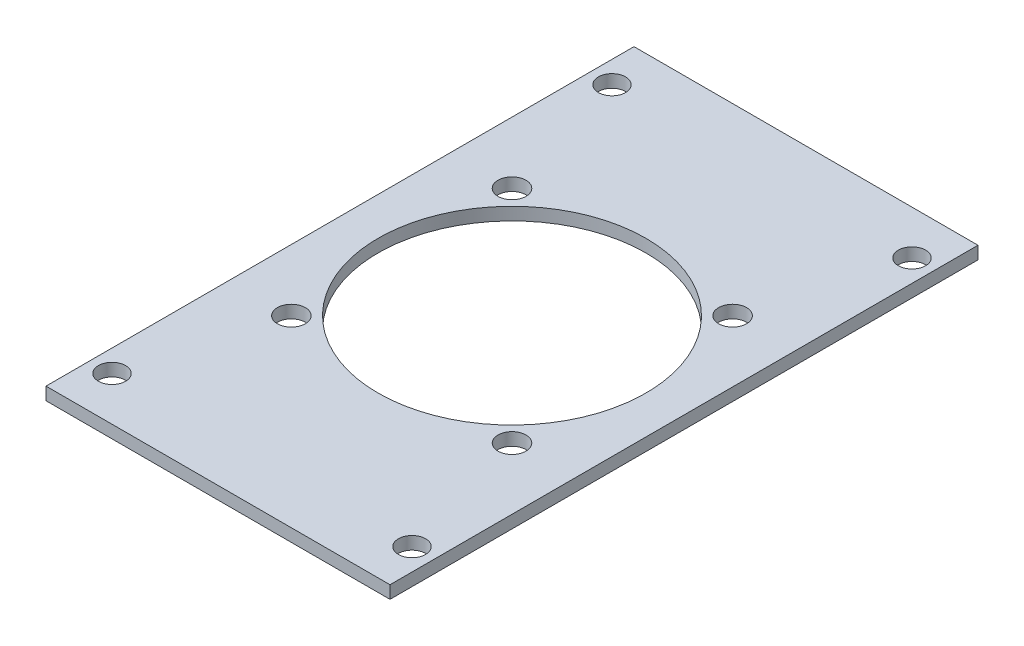
SolidWorks part; units mm, degrees
material "AISI 1045 Steel, cold drawn"
ref_plane "Frontal Plane" through (0, 0, 0) normal (0, 0, 1) x (1, 0, 0)
ref_plane "Horizontal Plane" through (0, 0, 0) normal (0, 1, 0) x (1, 0, 0)
ref_plane "Profile Plane" through (0, 0, 0) normal (1, 0, 0) x (0, 0, -1)
sketch "Sketch1" plane through (0, 0, 0) normal (0, 1, 0) x (1, 0, 0)
  line L1 (-43, -73.5) -> (43, -73.5)
  line L2 (-43, -73.5) -> (-43, 73.5)
  line L3 (-43, 73.5) -> (43, 73.5)
  line L4 (43, -73.5) -> (43, 73.5)
  line L5 (-43, -73.5) -> (43, 73.5) construction
  line L6 (-43, 73.5) -> (43, -73.5) construction
  circle A0 centre (0, 0) radius 33.5
  circle A1 centre (-37.5, -62.5) radius 3.4
  circle A2 centre (37.5, -62.5) radius 3.4
  circle A3 centre (-37.5, 62.5) radius 3.4
  circle A4 centre (37.5, 62.5) radius 3.4
  point P0 (0, 0)
  dimension "D1" = 67
  dimension "D5" = 6.8
  dimension "D2" = 86
  dimension "D3" = 147
  dimension "D4" = 75
  dimension "D6" = 125
  dimension "D7" = 62.5
  dimension "D8" = 37.5
extrude "Boss-Extrude1" add sketch "Sketch1" along normal blind 3.175
sketch "Sketch2" plane through (0, 3.175, 0) normal (0, 1, 0) x (1, 0, 0)
  line L0 (-27.5772, 27.5772) -> (0, 0) construction
  line L1 (0, 0) -> (0, 39) construction
  line L2 (0, 0) -> (-27.5772, 27.5772) construction
  circle A0 centre (0, 0) radius 39 construction
  circle A1 centre (-27.5772, 27.5772) radius 3.5
  circle A2 centre (27.5772, 27.5772) radius 3.5
  circle A3 centre (27.5772, -27.5772) radius 3.5
  circle A4 centre (-27.5772, -27.5772) radius 3.5
  dimension "D1" = 78
  dimension "D3" = 7
  dimension "D2" = 45
  dimension "D5" = 39
  dimension "D4" = 4
extrude "Cut-Extrude1" cut sketch "Sketch2" against normal blind 10
equation "\"WallThickness\"= 0.5cm"
equation "\"BottomPlateX\"= 3ft"
equation "\"BottomPlateZ\"= 2ft"
equation "\"BottomPlateHoleD\"=((\"ArmPlateX\")^2+(\"ArmPlateDepth\")^2)^.5+ 10mm"
equation "\"ActuatorPinD\"= 6.35mm"
equation "\"ActuatorPinL\"= 15cm"
equation "\"Box-X\"= 40cm"
equation "\"Box-Z\"= 20cm"
equation "\"Box-Y\"= 30cm"
equation "\"ArmPlateThickness\"= .125in"
equation "\"ArmPlateX\"= 18in"
equation "\"ArmPlateDepth\"= 7.1875in"
equation "\"DCMotor1D\"= 65mm"
equation "\"DCMotor1L\"= 215mm"
equation "\"DCMotor1ShaftL\"= 30mm"
equation "\"DCMotor2X\"= 68mm"
equation "\"DCMotor2D\"= 65mm"
equation "\"DCMotor2L\"= 208mm"
equation "\"DCMotor2ShaftL\"= 39mm"
equation "\"DCMotor2ShaftD\"= 15mm"
equation "\"BenchDepth\"= 5cm"
equation "\"BenchH\"= 10cm"
equation "\"BenchL\"= 15cm"
equation "\"PillowBlockW\"= 5cm"
equation "\"PillowBlockCenterH\"= \"DCMotor2X\"/2"
equation "\"EncoderRadius\"= 19mm"
equation "\"EncoderShaftL\"= 15mm"
equation "\"EncoderL\"= 33mm"
equation "\"EncoderHousingThickness\"= 7.5mm"
equation "\"TurntableID\"= 70mm"
equation "\"TurntableInner2*t\" = (\"TurntableOD\"-\"TurntableID\")*.25 - 1mm"
equation "\"TurntableInnerHoleRadius\"= \"TurntableID\"*.5 + \"TurntableInner2*t\"*.5"
equation "\"TurntableOD\"= 120mm"
equation "\"TurntableOuterHoleRadius\" = \"TurntableOD\"*.5 - ((\"TurntableOD\"-\"TurntableID\")*.25-.5mm)*.5"
equation "\"2525Height\" = 30cm"
equation "\"D1@Sketch1\"=\"DCMotor2D\"+2mm"
equation "\"D2@Sketch4\"=\"EncoderRadius\"+1.5cm"
equation "\"D1@Sketch4\"=\"EncoderRadius\"*2"
